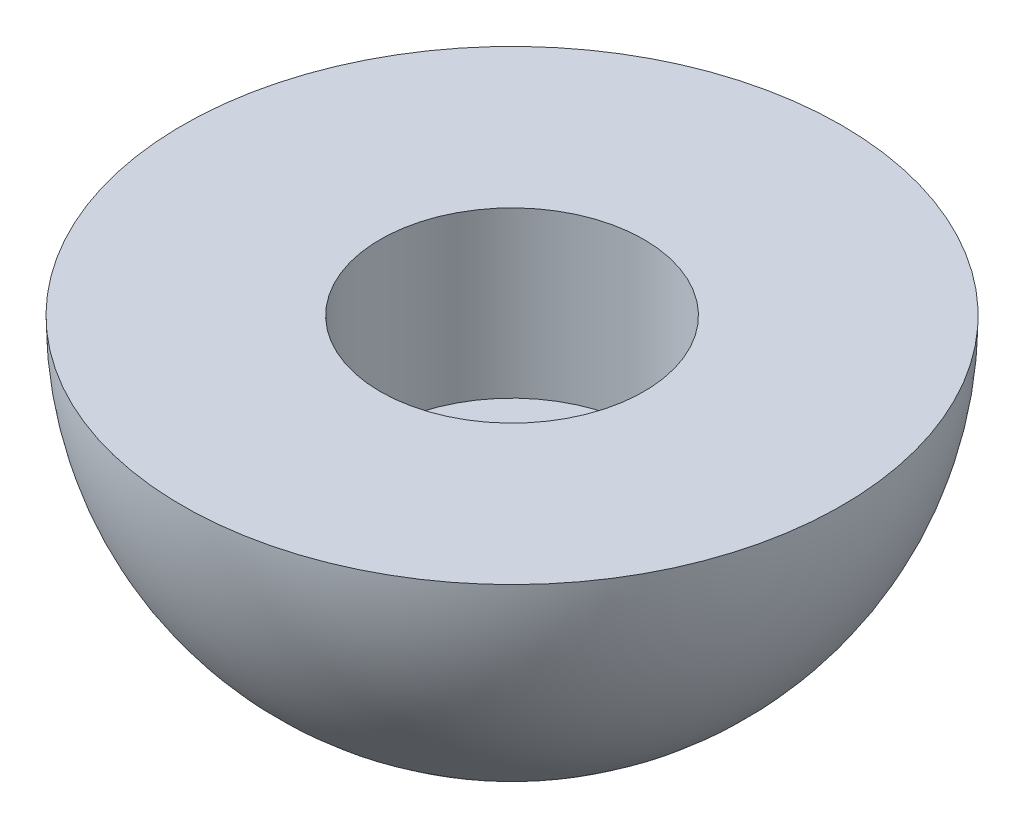
SolidWorks part; units mm, degrees
ref_plane "Front Plane" through (0, 0, 0) normal (0, 0, 1) x (1, 0, 0)
ref_plane "Top Plane" through (0, 0, 0) normal (0, 1, 0) x (1, 0, 0)
ref_plane "Right Plane" through (0, 0, 0) normal (1, 0, 0) x (0, 0, -1)
sketch "Sketch1" plane through (0, 0, 0) normal (0, 1, 0) x (1, 0, 0)
  line L0 (10, 0) -> (-10, 0)
  arc A0 (10, 0) -> (-10, 0) centre (0, 0) ccw
  dimension "D1" = 20
revolve "Revolve1" add sketch "Sketch1" angle 180 about L0
sketch "Sketch2" plane through (0, 0, 0) normal (0, 1, 0) x (1, 0, 0)
  circle A0 centre (0, 0) radius 4
  dimension "D1" = 8
extrude "Cut-Extrude1" cut sketch "Sketch2" against normal blind 5 and the other way through all
